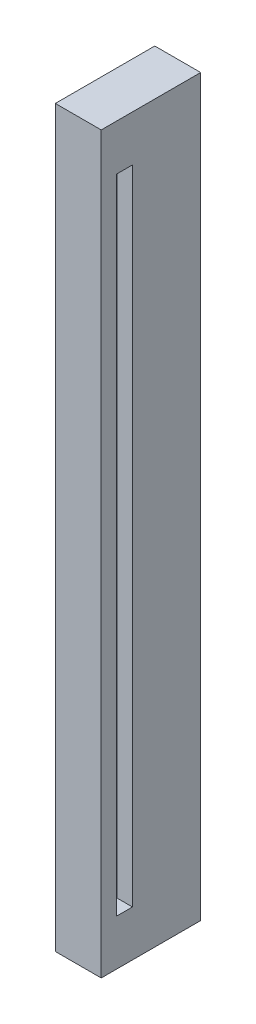
SolidWorks part; units mm, degrees
material "Pine"
ref_plane "Front Plane" through (0, 0, 0) normal (0, 0, 1) x (1, 0, 0)
ref_plane "Top Plane" through (0, 0, 0) normal (0, 1, 0) x (1, 0, 0)
ref_plane "Right Plane" through (0, 0, 0) normal (1, 0, 0) x (0, 0, -1)
sketch "Sketch1" plane through (0, 0, 0) normal (0, 0, 1) x (1, 0, 0)
  line L1 (-9.525, -152.4) -> (9.525, -152.4)
  line L2 (-9.525, -152.4) -> (-9.525, 152.4)
  line L3 (-9.525, 152.4) -> (9.525, 152.4)
  line L4 (9.525, -152.4) -> (9.525, 152.4)
  line L5 (-9.525, -152.4) -> (9.525, 152.4) construction
  line L6 (-9.525, 152.4) -> (9.525, -152.4) construction
  point P0 (0, 0)
  dimension "D1" = 19.05
  dimension "D2" = 304.8
extrude "Boss-Extrude1" add sketch "Sketch1" along normal blind 41.275
sketch "Sketch2" plane through (9.525, 0, 0) normal (1, 0, 0) x (0, 0, -1)
  line L1 (-34.925, 133.35) -> (-28.321, 133.35)
  line L2 (-34.925, 133.35) -> (-34.925, -133.35)
  line L3 (-34.925, -133.35) -> (-28.321, -133.35)
  line L4 (-28.321, 133.35) -> (-28.321, -133.35)
  line L6 (-41.275, -152.4) -> (-41.275, 152.4) construction
  line L8 (-41.275, 152.4) -> (0, 152.4) construction
  point P4 (-34.925, 128.5989)
  point P5 (-28.321, 0)
  point P7 (-34.925, -138.5836)
  point P10 (0, 0)
  dimension "D1" = 19.05
  dimension "D2" = 6.35
  dimension "D3" = 6.604
extrude "Cut-Extrude1" cut sketch "Sketch2" against normal blind 6.35
